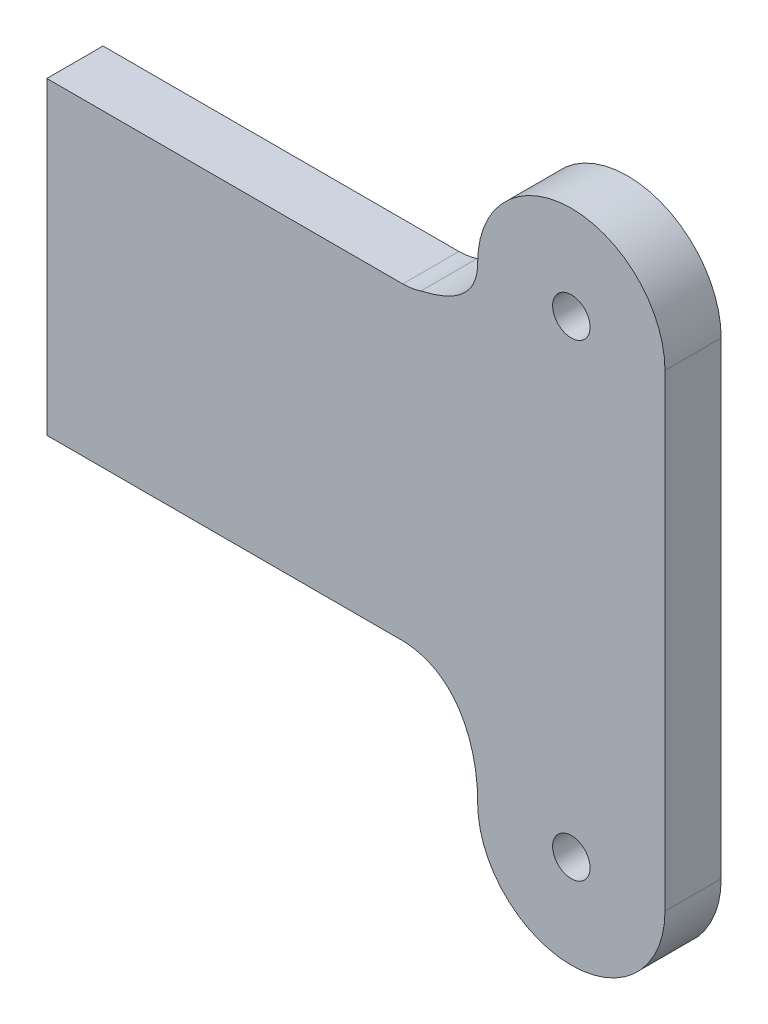
SolidWorks part; units mm, degrees
ref_plane "Front Plane" through (0, 0, 0) normal (0, 0, 1) x (1, 0, 0)
ref_plane "Top Plane" through (0, 0, 0) normal (0, 1, 0) x (1, 0, 0)
ref_plane "Right Plane" through (0, 0, 0) normal (1, 0, 0) x (0, 0, -1)
sketch "Sketch1" plane through (0, 0, 0) normal (0, 0, 1) x (1, 0, 0)
  line L0 (0, 0) -> (0, -10)
  line L1 (0, -10) -> (9, -10)
  line L2 (0, 0) -> (12, 0)
  line L3 (12, 0) -> (12, 2.5)
  line L4 (12, 2.5) -> (0, 2.5)
  line L5 (0, 2.5) -> (0, 6.5)
  line L6 (0, 6.5) -> (9, 6.5)
  line L7 (18, 14.5) -> (18, -20.5) construction
  line L8 (15, 14.5) -> (21, 14.5)
  line L9 (12, 11.5) -> (12, 9.5)
  line L10 (15, -20.5) -> (21, -20.5)
  line L11 (24, 11.5) -> (24, -17.5)
  line L12 (12, -13) -> (12, -17.5)
  arc A0 (12, -17.5) -> (15, -20.5) centre (15, -17.5) ccw
  arc A1 (21, -20.5) -> (24, -17.5) centre (21, -17.5) ccw
  arc A2 (15, 14.5) -> (12, 11.5) centre (15, 11.5) ccw
  arc A3 (21, 14.5) -> (24, 11.5) centre (21, 11.5) cw
  circle A4 centre (18, -15.5) radius 1
  circle A5 centre (18, 9.5) radius 1
  arc A6 (12, 9.5) -> (9, 6.5) centre (9, 9.5) cw
  arc A7 (9, -10) -> (12, -13) centre (9, -13) cw
  point P17 (24, -20.5)
  point P20 (12, 14.5)
  point P23 (24, 14.5)
  point P34 (12, -10)
  dimension "D8" = 3
  dimension "D10" = 2
  dimension "D11" = 2
  dimension "D5" = 3
  dimension "D7" = 3
  dimension "D13" = 5
  dimension "D1" = 2.5
  dimension "D2" = 10
  dimension "D3" = 12
  dimension "D4" = 12
  dimension "D6" = 4
  dimension "D9" = 35
  dimension "D12" = 12
  dimension "D14" = 5
extrude "Boss-Extrude1" add sketch "Sketch1" along normal blind 3
sketch "Sketch5" plane through (0, 0, 3) normal (0, 0, 1) x (1, 0, 0)
  line L0 (23, 9.5) -> (23, -15.5)
  line L1 (0, -10) -> (9, -10) construction
  line L2 (0, 0) -> (0, -10) construction
  line L3 (12, 0) -> (0, 0) construction
  line L4 (12, 2.5) -> (12, 0) construction
  line L5 (0, 2.5) -> (12, 2.5) construction
  line L6 (0, 6.5) -> (0, 2.5) construction
  line L7 (9, 6.5) -> (0, 6.5) construction
  line L8 (0, -10) -> (9, -10)
  line L9 (0, 0) -> (0, -10)
  line L10 (12, 0) -> (0, 0)
  line L11 (12, 2.5) -> (12, 0)
  line L12 (0, 2.5) -> (12, 2.5)
  line L13 (0, 6.5) -> (0, 2.5)
  line L14 (9, 6.5) -> (0, 6.5)
  arc A0 (23, 9.5) -> (13.0001, 9.4646) centre (18, 9.5) ccw
  arc A1 (13.0007, -15.4181) -> (23, -15.5) centre (18, -15.5) ccw
  circle A2 centre (18, 9.5) radius 1 construction
  circle A3 centre (18, 9.5) radius 1
  circle A4 centre (18, -15.5) radius 1 construction
  circle A5 centre (18, -15.5) radius 1
  spline S0 degree 2 poles (9, 6.5) (13.0232, 7.0001) (13, 9.5) knots 0 0 0 1 1 1
  spline S1 degree 3 poles (13, -15.5) (13.03, -13.2333) (12.1219, -10.0983) (9, -10) knots 0 0 0 0 1 1 1 1
  line M1 (12, 0) -> (0, 0)
  line M2 (0, 0) -> (0, -10)
  line M3 (0, -10) -> (9, -10)
  arc M4 (9, -10) -> (12, -13) centre (9, -13) cw
  arc M14 (12, 9.5) -> (9, 6.5) centre (9, 9.5) cw
  line M15 (9, 6.5) -> (0, 6.5)
  line M16 (0, 6.5) -> (0, 2.5)
  line M17 (0, 2.5) -> (12, 2.5)
  line M18 (12, 2.5) -> (12, 0)
  circle M19 centre (18, -15.5) radius 1
  circle M20 centre (18, 9.5) radius 1
  dimension "D1" = 10
extrude "Cut-Extrude2" cut sketch "Sketch5" against normal blind 10 flip side to cut contours S1 A1 L0 A0 S0 M14 M15 M16 M17 M18 M1 M2 M3 M4 M19 M20
sketch "Sketch7" plane through (0, 0, 0) normal (-1, 0, 0) x (0, 0, 1)
  line L0 (0, 0) -> (0, -10) construction
  line L1 (3, -10) -> (0, -10) construction
  line L2 (3, 0) -> (3, -10) construction
  line L3 (3, 0) -> (0, 0) construction
  line L4 (3, 6.5) -> (0, 6.5) construction
  line L5 (0, 6.5) -> (0, 2.5) construction
  line L6 (3, 2.5) -> (0, 2.5) construction
  line L7 (3, 6.5) -> (3, 2.5) construction
  line L8 (0, 0) -> (0, -10)
  line L9 (3, -10) -> (0, -10)
  line L10 (3, 0) -> (3, -10)
  line L11 (3, 0) -> (0, 0)
  line L12 (3, 6.5) -> (0, 6.5)
  line L13 (0, 6.5) -> (0, 2.5)
  line L14 (3, 2.5) -> (0, 2.5)
  line L15 (3, 6.5) -> (3, 2.5)
extrude "Boss-Extrude2" add sketch "Sketch7" along normal blind 10
sketch "Sketch8" plane through (0, 0, 0) normal (0, 1, 0) x (1, 0, 0)
  line L0 (-10, -3) -> (-10, 0) construction
  line L1 (12, -3) -> (12, 0) construction
  line L2 (12, 0) -> (-10, 0) construction
  line L3 (12, -3) -> (-10, -3) construction
  line L4 (-10, -3) -> (-10, 0)
  line L5 (12, -3) -> (12, 0)
  line L6 (12, 0) -> (-10, 0)
  line L7 (12, -3) -> (-10, -3)
extrude "Boss-Extrude3" add sketch "Sketch8" along normal up to next
